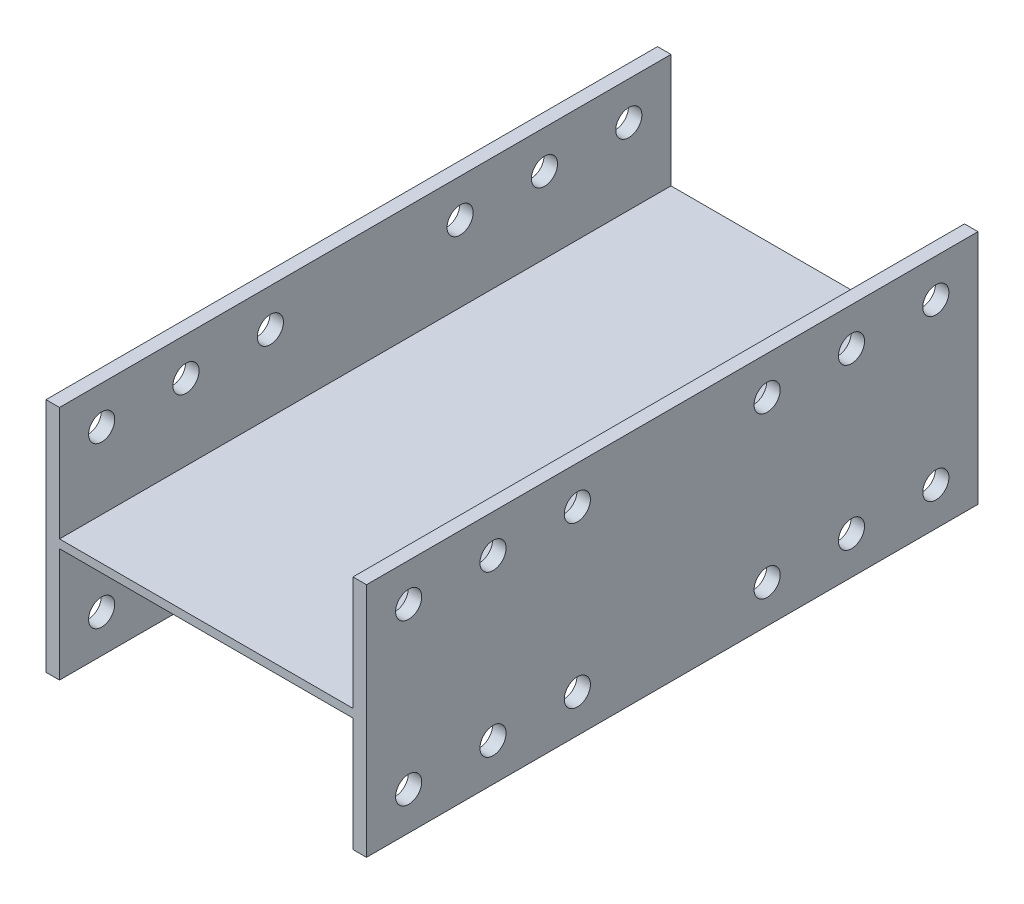
SolidWorks part; units mm, degrees
ref_plane "前视基准面" through (0, 0, 0) normal (0, 0, 1) x (1, 0, 0)
ref_plane "上视基准面" through (0, 0, 0) normal (0, 1, 0) x (1, 0, 0)
ref_plane "右视基准面" through (0, 0, 0) normal (1, 0, 0) x (0, 0, -1)
sketch "草图1" plane through (0, 0, 0) normal (0, 0, 1) x (1, 0, 0)
  line L2 (-174, 140) -> (-190, 140)
  line L3 (-190, 140) -> (-190, -140)
  line L4 (-190, -140) -> (-174, -140)
  line L5 (-174, -140) -> (-174, -5)
  line L6 (-174, 5) -> (174, 5)
  line L7 (174, -5) -> (174, -140)
  line L8 (174, -140) -> (190, -140)
  line L9 (190, -140) -> (190, 140)
  line L10 (190, 140) -> (174, 140)
  line L11 (174, 140) -> (174, 5)
  line L12 (174, -5) -> (-174, -5)
  line L14 (-46.1795, 0) -> (78.1266, 0) construction
  line L16 (0, 244.361) -> (0, -35.639) construction
  line L17 (-174, 5) -> (-174, 140)
  dimension "D1" = 16
  dimension "D2" = 280
  dimension "D3" = 380
  dimension "D4" = 10
extrude "拉伸1" add sketch "草图1" along normal mid plane 725
sketch "草图3" plane through (0, 0, 0) normal (1, 0, 0) x (0, 0, -1)
  line L1 (-386.9896, 0) -> (390.7992, 0) construction
  line L2 (-362.5, -140) -> (-362.5, 140) construction
  line L3 (-362.5, 140) -> (362.5, 140) construction
  line L5 (0, 193.2764) -> (0, -212.9913) construction
  circle A0 centre (-312.5, 95) radius 15.5
  circle A1 centre (-212.5, 95) radius 15.5
  circle A2 centre (-112.5, 95) radius 15.5
  circle A3 centre (-112.5, -95) radius 15.5
  circle A4 centre (-212.5, -95) radius 15.5
  circle A5 centre (-312.5, -95) radius 15.5
  circle A6 centre (312.5, -95) radius 15.5
  circle A7 centre (212.5, -95) radius 15.5
  circle A8 centre (112.5, -95) radius 15.5
  circle A9 centre (112.5, 95) radius 15.5
  circle A10 centre (212.5, 95) radius 15.5
  circle A11 centre (312.5, 95) radius 15.5
  dimension "D2" = 31
  dimension "D1" = 50
  dimension "D3" = 45
  dimension "D4" = 100
extrude "拉伸2" cut sketch "草图3" against normal through all and the other way through all
